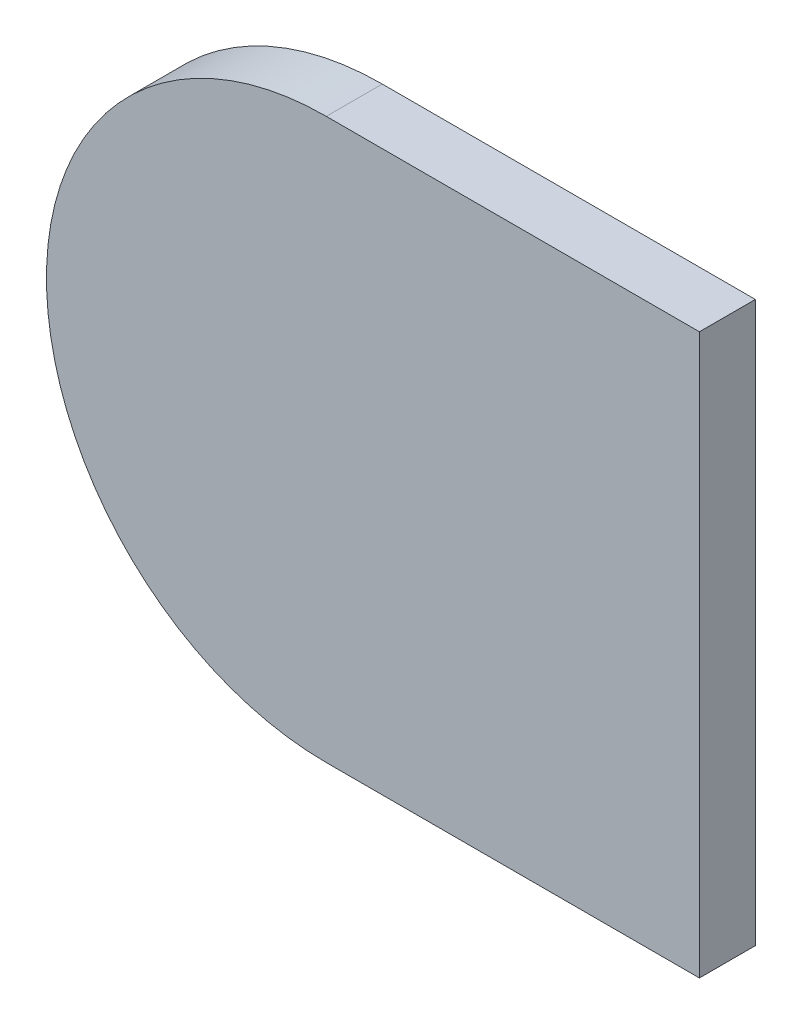
SolidWorks part; units mm, degrees
ref_plane "前视基准面" through (0, 0, 0) normal (0, 0, 1) x (1, 0, 0)
ref_plane "上视基准面" through (0, 0, 0) normal (0, 1, 0) x (1, 0, 0)
ref_plane "右视基准面" through (0, 0, 0) normal (1, 0, 0) x (0, 0, -1)
other "Configuration Table"
sketch "草图1" plane through (0, 0, 0) normal (0, 0, 1) x (1, 0, 0)
  line L0 (0, 0) -> (40, 0) construction
  line L1 (0, 30) -> (40, 30)
  line L2 (0, -30) -> (40, -30)
  line L3 (40, 30) -> (40, -30)
  arc A0 (0, 30) -> (0, -30) centre (0, 0) ccw
  arc A1 (40, -30) -> (40, 30) centre (40, 0) ccw
  point P3 (20, 0)
  dimension "D1" = 60
  dimension "D2" = 40
extrude "凸台-拉伸1" add sketch "草图1" along normal blind 6
sketch "草图2" plane through (0, 0, 0) normal (0, 0, -1) x (-1, 0, 0)
  circle A0 centre (0, 0) radius 18.75
  dimension "D1" = 37.5
extrude "切除-拉伸1" cut sketch "草图2" against normal blind 1
sketch "草图3" plane through (0, 0, 6) normal (0, 0, 1) x (1, 0, 0)
  line L1 (-11.8102, 11.8102) -> (11.8102, 11.8102)
  line L2 (-11.8102, 11.8102) -> (-11.8102, -11.8102)
  line L3 (-11.8102, -11.8102) -> (11.8102, -11.8102)
  line L4 (11.8102, 11.8102) -> (11.8102, -11.8102)
  line L5 (-11.8102, 11.8102) -> (11.8102, -11.8102) construction
  line L6 (-11.8102, -11.8102) -> (11.8102, 11.8102) construction
  point P0 (0, 0)
  dimension "D1" = 33.4044
